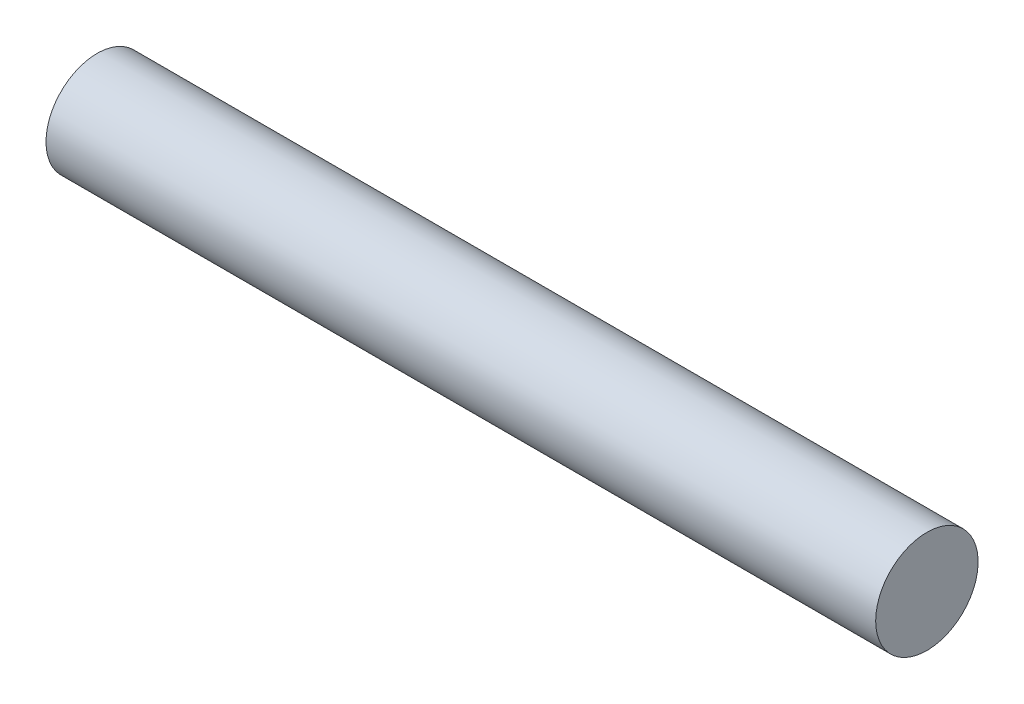
SolidWorks part; units mm, degrees
ref_plane "Front Plane" through (0, 0, 0) normal (0, 0, 1) x (1, 0, 0)
ref_plane "Top Plane" through (0, 0, 0) normal (0, 1, 0) x (1, 0, 0)
ref_plane "Right Plane" through (0, 0, 0) normal (1, 0, 0) x (0, 0, -1)
sketch "Sketch1" plane through (0, 0, 0) normal (0, 0, 1) x (1, 0, 0)
  line L1 (0, 0) -> (24.3, 0)
  line L2 (0, 0) -> (0, 1.5)
  line L3 (0, 1.5) -> (24.3, 1.5)
  line L4 (24.3, 0) -> (24.3, 1.5)
  dimension "D1" = 24.3
  dimension "D2" = 1.5
revolve "Revolve1" add sketch "Sketch1" angle 360 about L1
